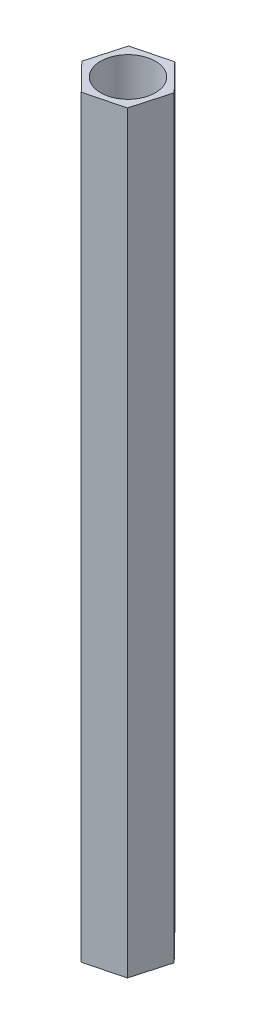
SolidWorks part; units mm, degrees
ref_plane "前视基准面" through (0, 0, 0) normal (0, 0, 1) x (1, 0, 0)
ref_plane "上视基准面" through (0, 0, 0) normal (0, 1, 0) x (1, 0, 0)
ref_plane "右视基准面" through (0, 0, 0) normal (1, 0, 0) x (0, 0, -1)
sketch "草图1" plane through (0, 0, 0) normal (0, 1, 0) x (1, 0, 0)
  line L1 (1.2116, -1.2377) -> (1.6777, 0.4304)
  line L2 (1.6777, 0.4304) -> (0.4661, 1.6682)
  line L3 (0.4661, 1.6682) -> (-1.2116, 1.2377)
  line L4 (-1.2116, 1.2377) -> (-1.6777, -0.4304)
  line L5 (-1.6777, -0.4304) -> (-0.4661, -1.6682)
  line L6 (-0.4661, -1.6682) -> (1.2116, -1.2377)
  circle A0 centre (0, 0) radius 1.5 construction
  dimension "D1" = 3
extrude "凸台-拉伸1" add sketch "草图1" along normal blind 34.39
sketch "草图2" plane through (0, 34.39, 0) normal (0, 1, 0) x (1, 0, 0)
  circle A0 centre (0, 0) radius 1.25
  dimension "D1" = 2.5
extrude "切除-拉伸1" cut sketch "草图2" against normal blind 34.39
